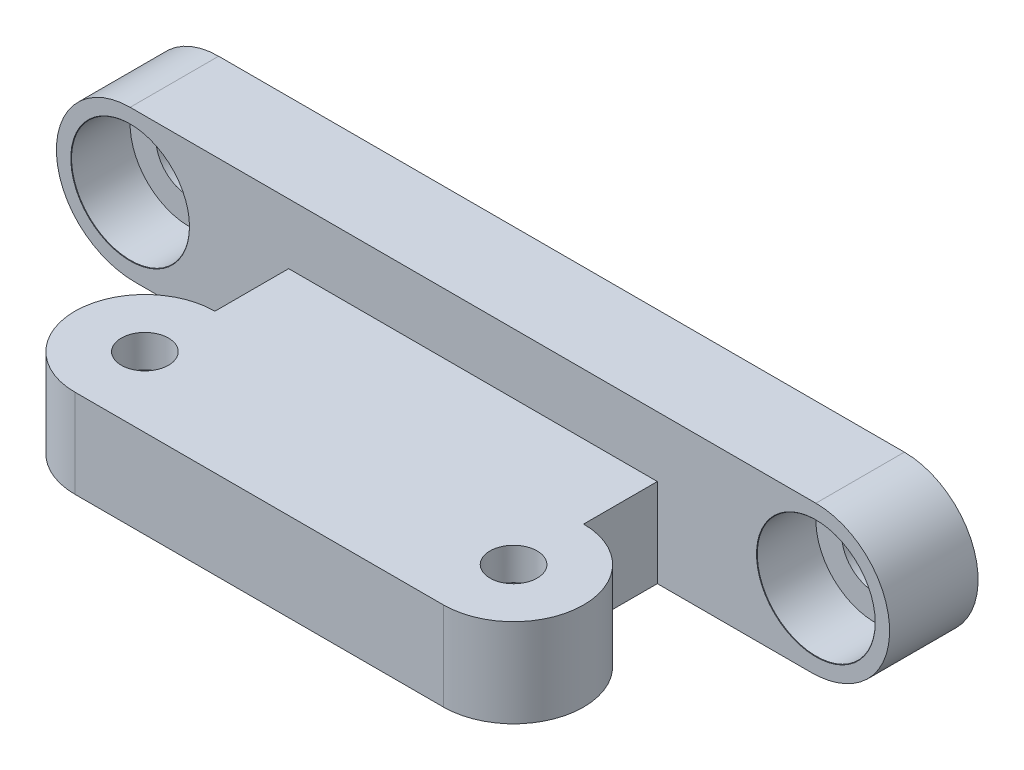
SolidWorks part; units mm, degrees
ref_plane "Front" through (0, 0, 0) normal (0, 0, 1) x (1, 0, 0)
ref_plane "Top" through (0, 0, 0) normal (0, 1, 0) x (1, 0, 0)
ref_plane "Right" through (0, 0, 0) normal (1, 0, 0) x (0, 0, -1)
sketch "Sketch1" plane through (0, 0, 0) normal (0, 1, 0) x (1, 0, 0)
  line L0 (-12.5, 0) -> (12.5, 0) construction
  line L3 (-12.5, -4.75) -> (12.5, -4.75)
  line L5 (-12.5, 4.75) -> (-12.5, 9.75)
  line L6 (-12.5, 9.75) -> (12.5, 9.75)
  line L7 (12.5, 9.75) -> (12.5, 4.75)
  arc A0 (12.5, -4.75) -> (12.5, 4.75) centre (12.5, 0) ccw
  arc A1 (-12.5, 4.75) -> (-12.5, -4.75) centre (-12.5, 0) ccw
  dimension "D3" = 4.75
  dimension "D1" = 25
  dimension "D2" = 5
extrude "Boss-Extrude1" add sketch "Sketch1" against normal blind 6
hole_wizard "M3 Clearance Hole1" positions "Sketch2" profile "Sketch3" hole size "M3" standard "ANSI Metric"
sketch "Sketch2" plane through (0, -6, 0) normal (0, -1, 0) x (-1, 0, 0)
  point P0 (12.5, 0)
  point P3 (-12.5, 0)
sketch "Sketch3" plane through (-12.5, -6, 0) normal (1, 0, 0) x (0, 0, -1)
  line L0 (0, 0) -> (0, 6)
  line L1 (0, 6) -> (1.6, 6)
  line L2 (1.6, 6) -> (1.6, 0)
  line L5 (1.6, 0) -> (0, 0)
  line L11 (0, -6.35) -> (0, 107.95) construction
  dimension "Thru Hole Dia." = 3.2
  dimension "Thru Hole Depth" = 6
sketch "Sketch7" plane through (0, -6, 0) normal (0, 1, 0) x (-1, 0, 0)
  circle A0 centre (12.5, 0) radius 2.75
  circle A1 centre (-12.5, 0) radius 2.75
  dimension "D1" = 5.5
extrude "Cut-Extrude1" cut sketch "Sketch7" along normal blind 3.8 draft 3
sketch "Sketch4" plane through (0, 0, -9.75) normal (0, 0, -1) x (-1, 0, 0)
  line L0 (23.25, 4.1) -> (-23.25, 4.1)
  line L5 (0, 0) -> (0, -0.9) construction
  line L6 (22.95, -6) -> (-22.95, -6)
  line L7 (23.25, -0.9) -> (-23.25, -0.9) construction
  line L14 (12.5, -6) -> (-12.5, -6) construction
  arc A0 (26.25, -4.9) -> (23.25, 4.1) centre (23.25, -0.9) ccw
  arc A2 (-26.25, -4.9) -> (-23.25, 4.1) centre (-23.25, -0.9) cw
  arc A3 (-22.95, -6) -> (-26.25, -4.9) centre (-22.95, -0.5) cw
  arc A4 (22.95, -6) -> (26.25, -4.9) centre (22.95, -0.5) ccw
  dimension "D3" = 5.5
  dimension "D1" = 5
  dimension "D2" = 0.9
  dimension "D5" = 46.5
extrude "Boss-Extrude2" add sketch "Sketch4" along normal blind 6
hole_wizard "CBORE for M4 SHCS1" positions "Sketch8" profile "Sketch9" counterbore size "M4" standard "ANSI Metric"
sketch "Sketch8" plane through (0, 0, -9.75) normal (0, 0, 1) x (1, 0, 0)
  point P0 (23.25, -0.9)
  point P3 (-23.25, -0.9)
sketch "Sketch9" plane through (23.25, -0.9, -9.75) normal (1, 0, 0) x (0, -1, 0)
  line L0 (0, 0) -> (0, 11.3519)
  line L1 (0, 11.3519) -> (2.25, 10)
  line L2 (2.25, 10) -> (2.25, 4)
  line L3 (2.25, 4) -> (4, 4)
  line L5 (4, 4) -> (4, 0.025)
  line L6 (4, 0.025) -> (4.025, 0)
  line L7 (4.025, 0) -> (0, 0)
  line L8 (-4, 0.025) -> (-4.025, 0) construction
  line L10 (0, 11.3519) -> (-2.25, 10) construction
  line L11 (0, -6.35) -> (0, 107.95) construction
  dimension "Hole Dia." = 4.5
  dimension "Hole Depth" = 10
  dimension "C'Bore Dia." = 8
  dimension "C'Bore Depth" = 4
  dimension "Near C'Sink Dia." = 8.05
  dimension "Near C'Sink Angle" = 90
  dimension "Drill Angle" = 118
